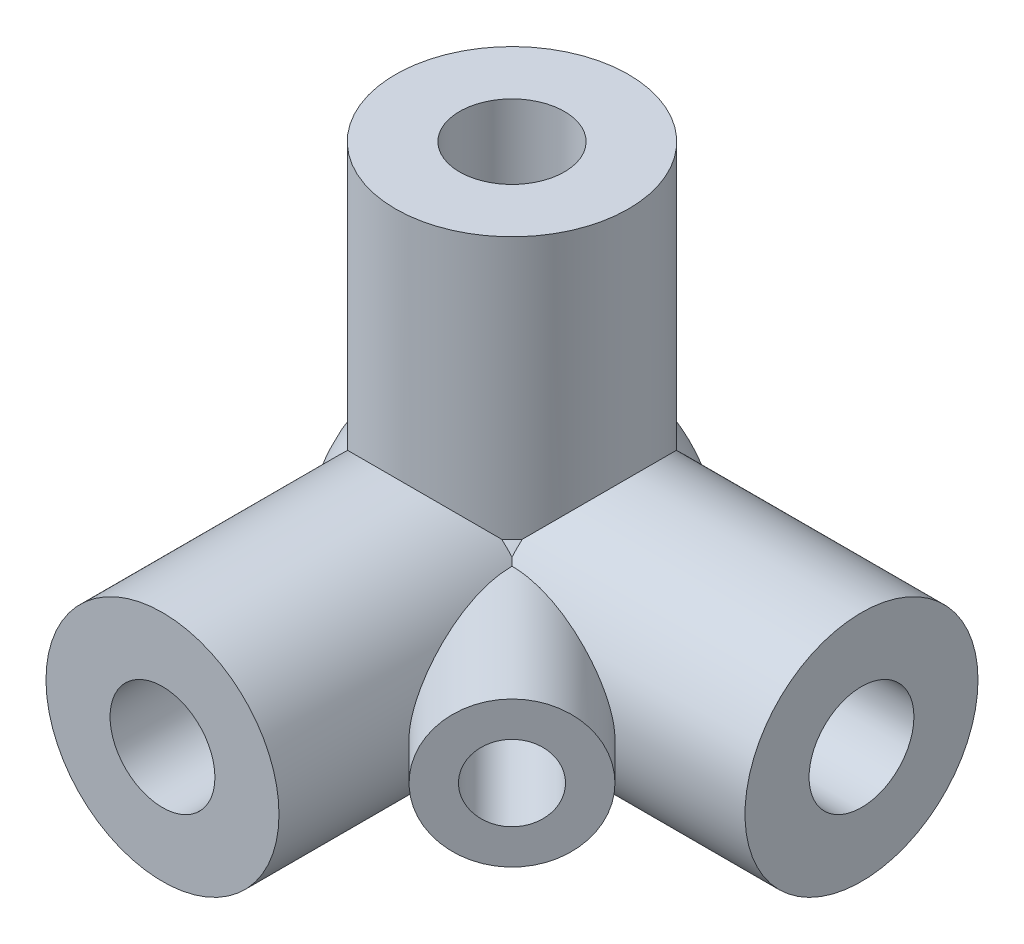
SolidWorks part; units mm, degrees
ref_plane "前视基准面" through (0, 0, 0) normal (0, 0, 1) x (1, 0, 0)
ref_plane "上视基准面" through (0, 0, 0) normal (0, 1, 0) x (1, 0, 0)
ref_plane "右视基准面" through (0, 0, 0) normal (1, 0, 0) x (0, 0, -1)
sketch "草图2" plane through (0, 0, 0) normal (0, 1, 0) x (1, 0, 0)
  circle A0 centre (0, 0) radius 2
  dimension "D1" = 4
extrude "凸台-拉伸1" add sketch "草图2" along normal blind 6
sketch "草图3" plane through (0, 0, 0) normal (0, 0, 1) x (1, 0, 0)
  circle A0 centre (0, 0) radius 2
  dimension "D1" = 4
extrude "凸台-拉伸2" add sketch "草图3" along normal blind 6
sketch "草图4" plane through (0, 0, 0) normal (1, 0, 0) x (0, 0, -1)
  circle A0 centre (0, 0) radius 2
  dimension "D1" = 4
extrude "凸台-拉伸3" add sketch "草图4" along normal blind 6
sketch "草图5" plane through (0, 0, 0) normal (0, 1, 0) x (1, 0, 0)
  line L0 (0, 2.5) -> (0, -2.5)
  arc A0 (0, 2.5) -> (0, -2.5) centre (0, 0) ccw
  arc A1 (0, -2.5) -> (0, 2.5) centre (0, 0) ccw construction
  dimension "D1" = 5
revolve "旋转3" add sketch "草图5" angle 360 about L0
sketch "草图6" plane through (0, 6, 0) normal (0, 1, 0) x (1, 0, 0)
  circle A0 centre (0, 0) radius 0.9
  dimension "D1" = 1.8
extrude "切除-拉伸1" cut sketch "草图6" against normal blind 5
sketch "草图9" plane through (0, 0, 0) normal (0, 1, 0) x (1, 0, 0)
  line L0 (0, 0) -> (10.0506, 0) construction
  line L1 (0, 0) -> (0, -11.034) construction
  line L2 (0, 0) -> (12.0486, -12.0486) construction
  dimension "D1" = 45
ref_plane "基准面1" through (0, 0, 0) normal (0.7071, 0, 0.7071) x (0.7071, 0, -0.7071)
sketch "草图10" plane through (0, 0, 0) normal (0.7071, 0, 0.7071) x (0.7071, 0, -0.7071)
  circle A0 centre (0, 0) radius 1.25
  dimension "D1" = 2.5
extrude "凸台-拉伸4" add sketch "草图10" along normal blind 5
sketch "草图11" plane through (0, 0, 0) normal (0, 0, 1) x (1, 0, 0)
  line L0 (0, 11.886) -> (0, 0) construction
  line L1 (0, 0) -> (10.8474, 10.8474) construction
  dimension "D1" = 45
sketch "草图12" plane through (0, 0, 0) normal (1, 0, 0) x (0, 0, -1)
  line L0 (0, 0) -> (-9.5688, 9.5688) construction
  line L1 (0, 11.886) -> (0, 0) construction
  dimension "D1" = 45
ref_plane "基准面3" through (0, 0, 0) normal (0, 0.7071, 0.7071) x (1, 0, 0)
sketch "草图7" plane through (6, 0, 0) normal (1, 0, 0) x (0, 0, -1)
  circle A0 centre (0, 0) radius 0.9
  dimension "D1" = 1.8
extrude "切除-拉伸2" cut sketch "草图7" against normal blind 5
sketch "草图8" plane through (0, 0, 6) normal (0, 0, 1) x (1, 0, 0)
  circle A0 centre (0, 0) radius 0.9
  dimension "D1" = 1.8
extrude "切除-拉伸3" cut sketch "草图8" against normal blind 5
sketch "草图14" plane through (3.5355, 0, 3.5355) normal (0.7071, 0, 0.7071) x (0.7071, 0, -0.7071)
  circle A0 centre (0, 0) radius 0.65
  dimension "D1" = 1.3
extrude "切除-拉伸4" cut sketch "草图14" against normal blind 3
equation "\"m\"= 2"
